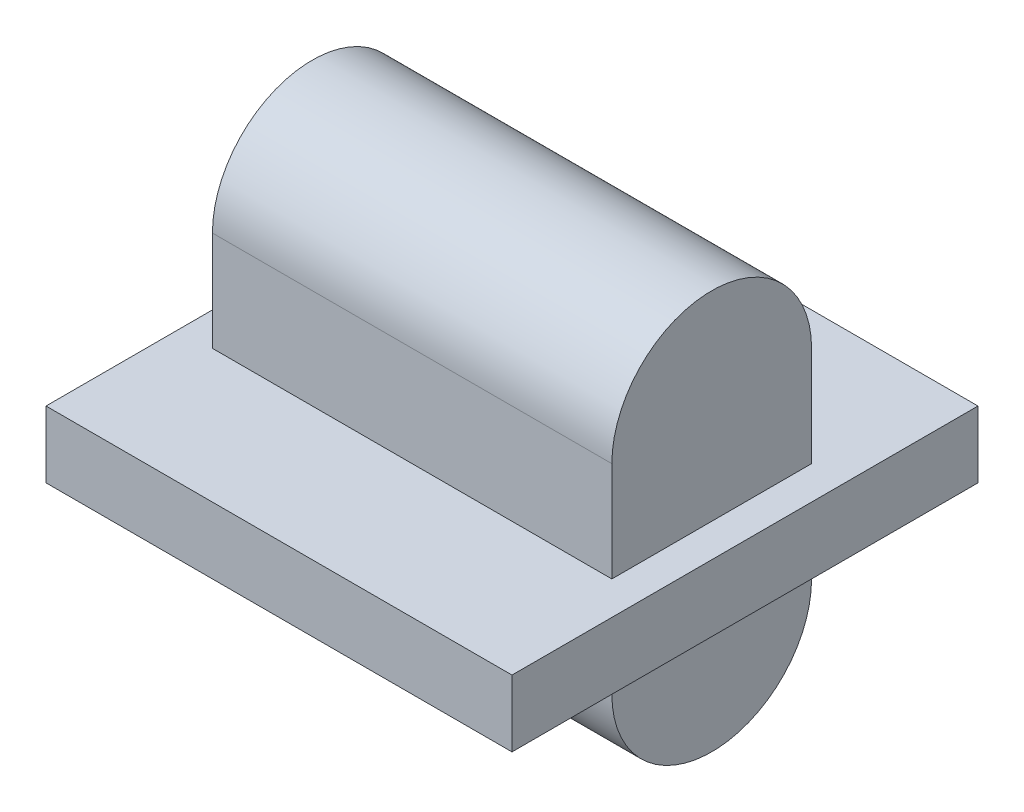
SolidWorks part; units mm, degrees
material "Plain Carbon Steel"
ref_plane "Front Plane" through (0, 0, 0) normal (0, 0, 1) x (1, 0, 0)
ref_plane "Top Plane" through (0, 0, 0) normal (0, 1, 0) x (1, 0, 0)
ref_plane "Right Plane" through (0, 0, 0) normal (1, 0, 0) x (0, 0, -1)
sketch "Sketch1" plane through (0, 0, 0) normal (0, 1, 0) x (1, 0, 0)
  line L1 (88.9, -88.9) -> (-88.9, -88.9)
  line L2 (88.9, -88.9) -> (88.9, 88.9)
  line L3 (88.9, 88.9) -> (-88.9, 88.9)
  line L4 (-88.9, -88.9) -> (-88.9, 88.9)
  line L5 (88.9, -88.9) -> (-88.9, 88.9) construction
  line L6 (88.9, 88.9) -> (-88.9, -88.9) construction
  point P0 (0, 0)
  dimension "D1" = 177.8
  dimension "D2" = 177.8
extrude "Boss-Extrude1" add sketch "Sketch1" along normal mid plane 25.4
sketch "Sketch2" plane through (0, 0, 0) normal (1, 0, 0) x (0, 0, -1)
  line L0 (0, -25.4) -> (0, 50.8) construction
  line L1 (-88.9, 12.7) -> (88.9, 12.7) construction
  line L2 (-38.1, -25.4) -> (-38.1, 50.8)
  line L3 (38.1, -25.4) -> (38.1, 50.8)
  arc A0 (-38.1, -25.4) -> (38.1, -25.4) centre (0, -25.4) ccw
  arc A1 (38.1, 50.8) -> (-38.1, 50.8) centre (0, 50.8) ccw
  point P4 (0, 12.7)
  point P9 (0, 12.7)
  point P10 (0, 12.7)
  dimension "D1" = 76.2
  dimension "D2" = 152.4
extrude "Boss-Extrude2" add sketch "Sketch2" along normal mid plane 152.4
